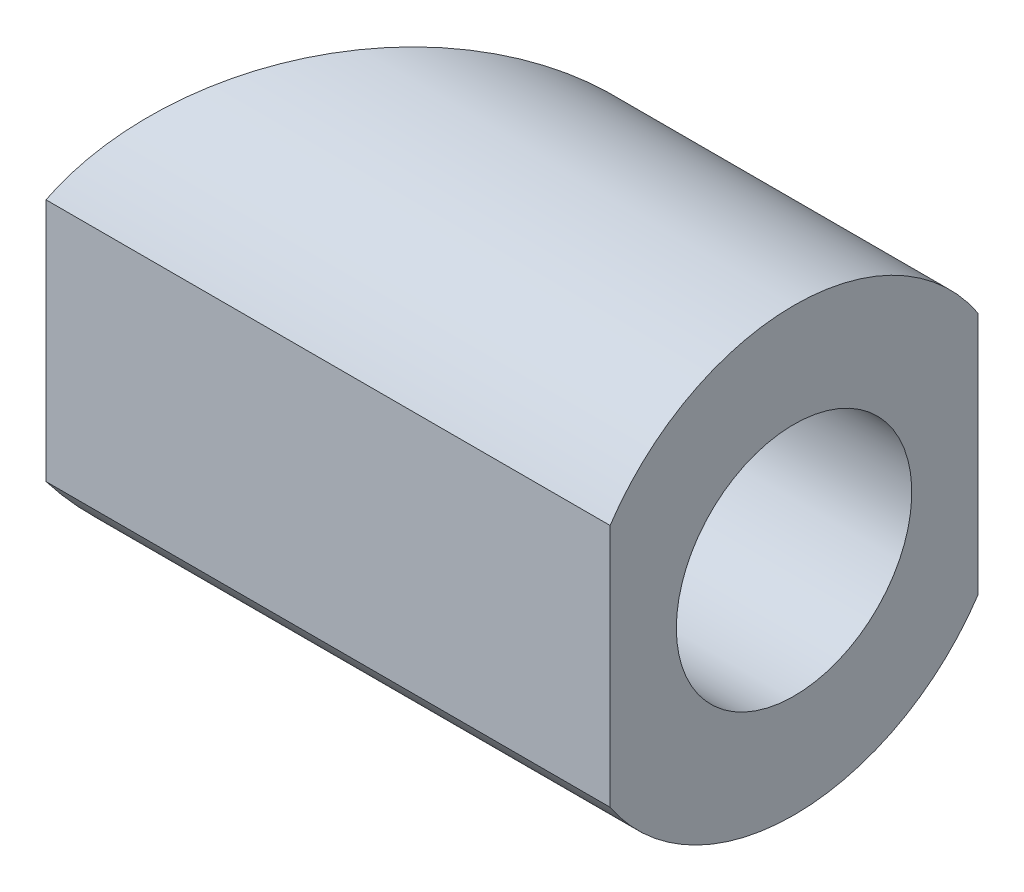
SolidWorks part; units mm, degrees
ref_plane "Front Plane" through (0, 0, 0) normal (0, 0, 1) x (1, 0, 0)
ref_plane "Top Plane" through (0, 0, 0) normal (0, 1, 0) x (1, 0, 0)
ref_plane "Right Plane" through (0, 0, 0) normal (1, 0, 0) x (0, 0, -1)
sketch "Sketch1" plane through (0, 0, 0) normal (0, 0, 1) x (1, 0, 0)
  line L0 (0, 0) -> (0, 1.6)
  line L1 (0, 1.6) -> (4, 1.6)
  line L2 (4, 1.6) -> (4, 3)
  line L3 (4, 3) -> (-4, 3)
  line L4 (-4, 3) -> (-4, 0)
  line L5 (-4, 0) -> (0, 0)
  line L6 (0, 0) -> (7.6771, 0) construction
  dimension "D1" = 3.2
  dimension "D2" = 4
  dimension "D3" = 4
  dimension "D4" = 1.4
revolve "Revolve1" add sketch "Sketch1" angle 360 about L6
sketch "Sketch2" plane through (0, 0, 0) normal (0, 1, 0) x (1, 0, 0)
  line L0 (-4, -3) -> (0, 3)
  line L1 (4, 3) -> (-4, 3) construction
  line L2 (0, 3) -> (-4, 3)
  line L3 (-4, 3) -> (-4, -3)
extrude "Cut-Extrude1" cut sketch "Sketch2" against normal through all both and the other way through all
sketch "Sketch3" plane through (0, 0, 0) normal (0, 1, 0) x (1, 0, 0)
  line L0 (0, 3) -> (-4, -3) construction
  line L1 (4, -3) -> (-4, -3)
  line L2 (4, -3) -> (4, -2.5)
  line L3 (4, -2.5) -> (-4, -2.5)
  line L4 (-4, -3) -> (-4, -2.5)
  line L5 (4, 3) -> (-0.3333, 3)
  line L6 (4, 3) -> (4, 2.5)
  line L7 (4, 2.5) -> (-0.3333, 2.5)
  line L8 (-0.3333, 3) -> (-0.3333, 2.5)
  dimension "D1" = 0.5
extrude "Cut-Extrude2" cut sketch "Sketch3" against normal through all both and the other way through all
fillet "Fillet1" [suppressed] radius 0.2
